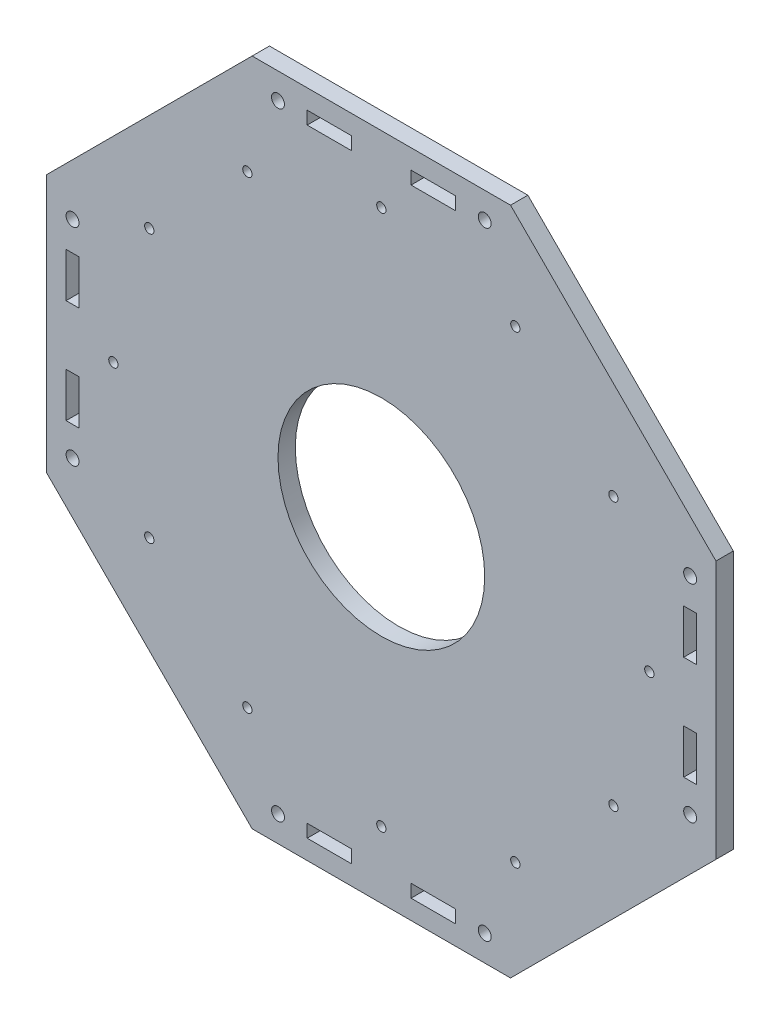
SolidWorks part; units mm, degrees
ref_plane "Front Plane" through (0, 0, 0) normal (0, 0, 1) x (1, 0, 0)
ref_plane "Top Plane" through (0, 0, 0) normal (0, 1, 0) x (1, 0, 0)
ref_plane "Right Plane" through (0, 0, 0) normal (1, 0, 0) x (0, 0, -1)
sketch "Sketch1" plane through (0, 0, 0) normal (0, 0, 1) x (1, 0, 0)
  line L0 (0, 145.4035) -> (0, -131.6744) construction
  line L1 (-213.8408, 0) -> (158.0925, 0) construction
  line L3 (0, 0) -> (88.9504, 88.9504) construction
  circle A0 centre (0, 0) radius 109.5
  circle A10 centre (0, 0) radius 40
  circle A11 centre (0, 103.7) radius 1.8
  circle A12 centre (51.85, 89.8068) radius 1.8
  circle A13 centre (89.8068, 51.85) radius 1.8
  circle A14 centre (103.7, 0) radius 1.8
  circle A15 centre (89.8068, -51.85) radius 1.8
  circle A16 centre (51.85, -89.8068) radius 1.8
  circle A17 centre (0, -103.7) radius 1.8
  circle A18 centre (-51.85, -89.8068) radius 1.8
  circle A19 centre (-89.8068, -51.85) radius 1.8
  circle A20 centre (-103.7, 0) radius 1.8
  circle A21 centre (-89.8068, 51.85) radius 1.8
  circle A22 centre (-51.85, 89.8068) radius 1.8
  point P36 (0, 0)
  point P79 (0, 0)
  point P100 (-0.0144, -0.0277)
  dimension "D1" = 219
  dimension "D2" = 3.6
  dimension "D3" = 103.7
  dimension "D9" = 80
  dimension "D8" = 45
extrude "Boss-Extrude1" add sketch "Sketch1" along normal blind 6.7
sketch "Sketch2" plane through (0, 0, 6.7) normal (0, 0, 1) x (1, 0, 0)
  line L0 (0, 148.5307) -> (0, -131.4586) construction
  line L1 (-156.9551, 0) -> (147.7737, 0) construction
  line L2 (-10, -109.5) -> (10, -109.5)
  line L3 (-10, 129.5) -> (10, 129.5)
  line L4 (-10, 129.5) -> (-10, 109.5)
  line L5 (-10, 109.5) -> (10, 109.5)
  line L6 (10, 129.5) -> (10, 109.5)
  line L7 (10, -129.5) -> (10, -109.5)
  line L8 (-10, -129.5) -> (10, -129.5)
  line L9 (-10, -129.5) -> (-10, -109.5)
  circle A0 centre (0, 0) radius 87.5
  circle A1 centre (0, 69.25) radius 5
  circle A2 centre (0, 0) radius 109.5
  dimension "D1" = 175
  dimension "D2" = 10
  dimension "D3" = 69.25
  dimension "D4" = 219
  dimension "D5" = 20
  dimension "D6" = 20
  dimension "D7" = 10
  dimension "D8" = 109.5
sketch "Sketch3" plane through (0, 0, 6.7) normal (0, 0, 1) x (1, 0, 0)
  line L0 (0, 124.0178) -> (0, -142.2429) construction
  line L1 (0, 148.5307) -> (0, -131.4586) construction
  line L2 (0, 0) -> (-33.4848, 80.8395) construction
  line L3 (-34.3935, 62.1283) -> (-40.7356, 77.4394) construction
  circle A1 centre (-32.0765, 77.4394) radius 1.5
  circle A2 centre (32.0765, 77.4394) radius 1.5
  circle A3 centre (83.1027, -10.9407) radius 1.5
  circle A4 centre (51.0263, -66.4987) radius 1.5
  circle A5 centre (-51.0263, -66.4987) radius 1.5
  circle A6 centre (-83.1027, -10.9407) radius 1.5
  point P10 (-37.5646, 69.7839)
  point P25 (0, 0)
  dimension "D1" = 3
  dimension "D4" = 3
  dimension "D2" = 22.5
  dimension "D3" = 8
sketch "Sketch4" plane through (0, 0, 0) normal (0, 0, 1) x (1, 0, 0)
  line L0 (0, 165.267) -> (0, -156.9001) construction
  line L1 (-182.9205, 0) -> (170.0769, 0) construction
  line L2 (50, 129.5) -> (-50, 129.5)
  line L10 (-63.7286, 119.5) -> (107.1322, 119.5) construction
  line L11 (-10, 141.5075) -> (-10, 100.4621) construction
  line L12 (28.7, 117) -> (11.5, 117)
  line L13 (-28.7, 122) -> (-11.5, 122)
  line L14 (-28.7, 122) -> (-28.7, 117)
  line L15 (-28.7, 117) -> (-11.5, 117)
  line L16 (-11.5, 122) -> (-11.5, 117)
  line L17 (11.5, 122) -> (11.5, 117)
  line L18 (28.7, 122) -> (11.5, 122)
  line L19 (28.7, 122) -> (28.7, 117)
  line L28 (129.5, -50) -> (129.5, 50)
  line L29 (-50, -129.5) -> (50, -129.5)
  line L30 (-129.5, 50) -> (-129.5, -50)
  line L31 (-50, 129.5) -> (-129.5, 50)
  line L34 (50, 129.5) -> (129.5, 50)
  line L36 (129.5, -50) -> (50, -129.5)
  line L38 (-50, -129.5) -> (-129.5, -50)
  line L44 (122, 28.7) -> (117, 28.7)
  line L45 (122, 28.7) -> (122, 11.5)
  line L46 (122, 11.5) -> (117, 11.5)
  line L47 (117, 28.7) -> (117, 11.5)
  line L48 (117, -28.7) -> (117, -11.5)
  line L49 (122, -11.5) -> (117, -11.5)
  line L50 (122, -28.7) -> (122, -11.5)
  line L51 (122, -28.7) -> (117, -28.7)
  line L52 (28.7, -122) -> (28.7, -117)
  line L53 (28.7, -122) -> (11.5, -122)
  line L54 (11.5, -122) -> (11.5, -117)
  line L55 (28.7, -117) -> (11.5, -117)
  line L56 (-28.7, -117) -> (-11.5, -117)
  line L57 (-11.5, -122) -> (-11.5, -117)
  line L58 (-28.7, -122) -> (-11.5, -122)
  line L59 (-28.7, -122) -> (-28.7, -117)
  line L60 (-122, -28.7) -> (-117, -28.7)
  line L61 (-122, -28.7) -> (-122, -11.5)
  line L62 (-122, -11.5) -> (-117, -11.5)
  line L63 (-117, -28.7) -> (-117, -11.5)
  line L64 (-117, 28.7) -> (-117, 11.5)
  line L65 (-122, 11.5) -> (-117, 11.5)
  line L66 (-122, 28.7) -> (-122, 11.5)
  line L67 (-122, 28.7) -> (-117, 28.7)
  circle A0 centre (0, 0) radius 109.5 construction
  circle A1 centre (0, 0) radius 109.5
  circle A3 centre (40, 119.5) radius 2.5
  circle A14 centre (-40, 119.5) radius 2.5
  circle A21 centre (119.5, 40) radius 2.5
  circle A22 centre (119.5, -40) radius 2.5
  circle A23 centre (40, -119.5) radius 2.5
  circle A24 centre (-40, -119.5) radius 2.5
  circle A25 centre (-119.5, -40) radius 2.5
  circle A26 centre (-119.5, 40) radius 2.5
  point P15 (0, 129.5)
  point P17 (128, 0)
  point P18 (-128, 0)
  point P19 (0, -129.5)
  point P39 (0, 0)
  point P45 (-11.5, 119.5)
  point P47 (0, 0)
  point P68 (0, 0)
  point P78 (0, 0)
  point P80 (0, 0)
  dimension "D1" = 129.5
  dimension "D5" = 5
  dimension "D6" = 40
  dimension "D3" = 50
  dimension "D7" = 10
  dimension "D9" = 10
  dimension "D10" = 17.2
  dimension "D11" = 1.5
  dimension "D12" = 5
  dimension "D13" = 2.5
extrude "Boss-Extrude2" add sketch "Sketch4" along normal blind 6.7
